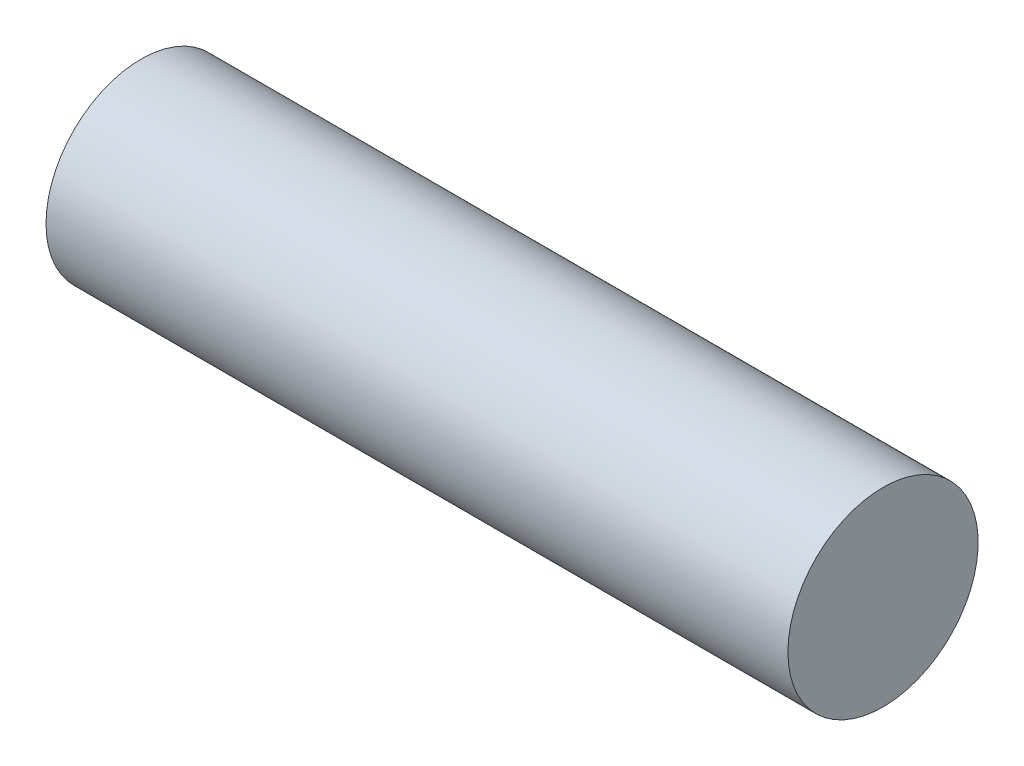
SolidWorks part; units mm, degrees
material "AISI 304"
ref_plane "Front Plane" through (0, 0, 0) normal (0, 0, 1) x (1, 0, 0)
ref_plane "Top Plane" through (0, 0, 0) normal (0, 1, 0) x (1, 0, 0)
ref_plane "Right Plane" through (0, 0, 0) normal (1, 0, 0) x (0, 0, -1)
sketch "Sketch1" plane through (0, 0, 0) normal (0, 1, 0) x (1, 0, 0)
  line L0 (-12.3825, 0) -> (12.3825, 0)
  line L1 (-12.3825, -3.175) -> (12.3825, -3.175)
  line L2 (-12.3825, -3.175) -> (-12.3825, 3.175)
  line L3 (-12.3825, 3.175) -> (12.3825, 3.175)
  line L4 (12.3825, -3.175) -> (12.3825, 3.175)
  line L5 (-12.3825, -3.175) -> (12.3825, 3.175) construction
  line L6 (-12.3825, 3.175) -> (12.3825, -3.175) construction
  point P0 (0, 0)
  dimension "D1" = 6.35
  dimension "D2" = 24.765
revolve "Revolve1" add sketch "Sketch1" angle 360 about L0
